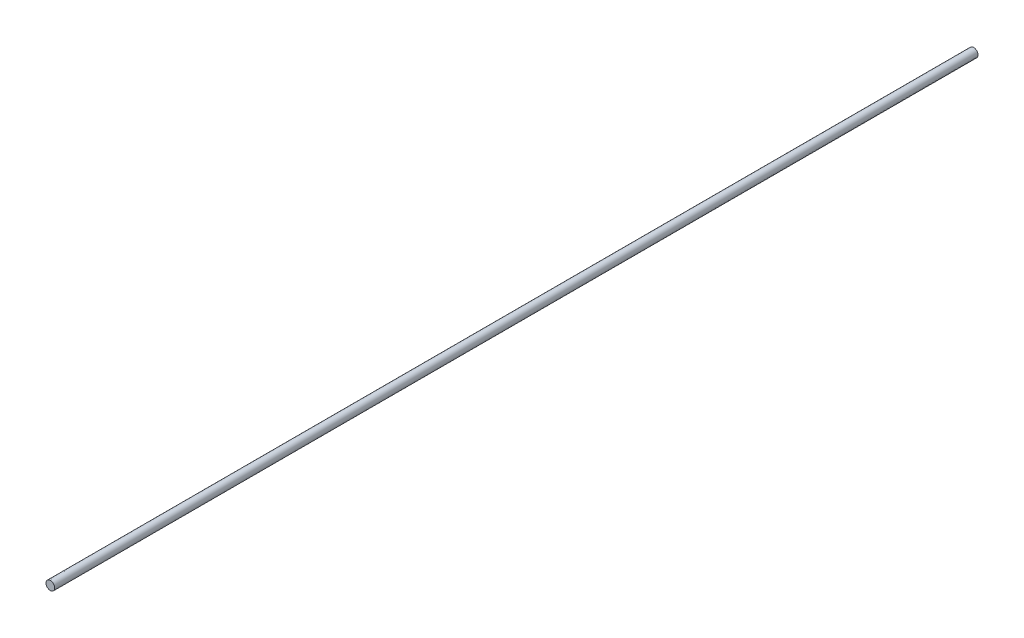
SolidWorks part; units mm, degrees
ref_plane "Front Plane" through (0, 0, 0) normal (0, 0, 1) x (1, 0, 0)
ref_plane "Top Plane" through (0, 0, 0) normal (0, 1, 0) x (1, 0, 0)
ref_plane "Right Plane" through (0, 0, 0) normal (1, 0, 0) x (0, 0, -1)
sketch "Sketch2" plane through (0, 0, 0) normal (0, 0, 1) x (1, 0, 0)
  circle A0 centre (0, 0) radius 4
extrude "Boss-Extrude1" add sketch "Sketch2" along normal mid plane 845
